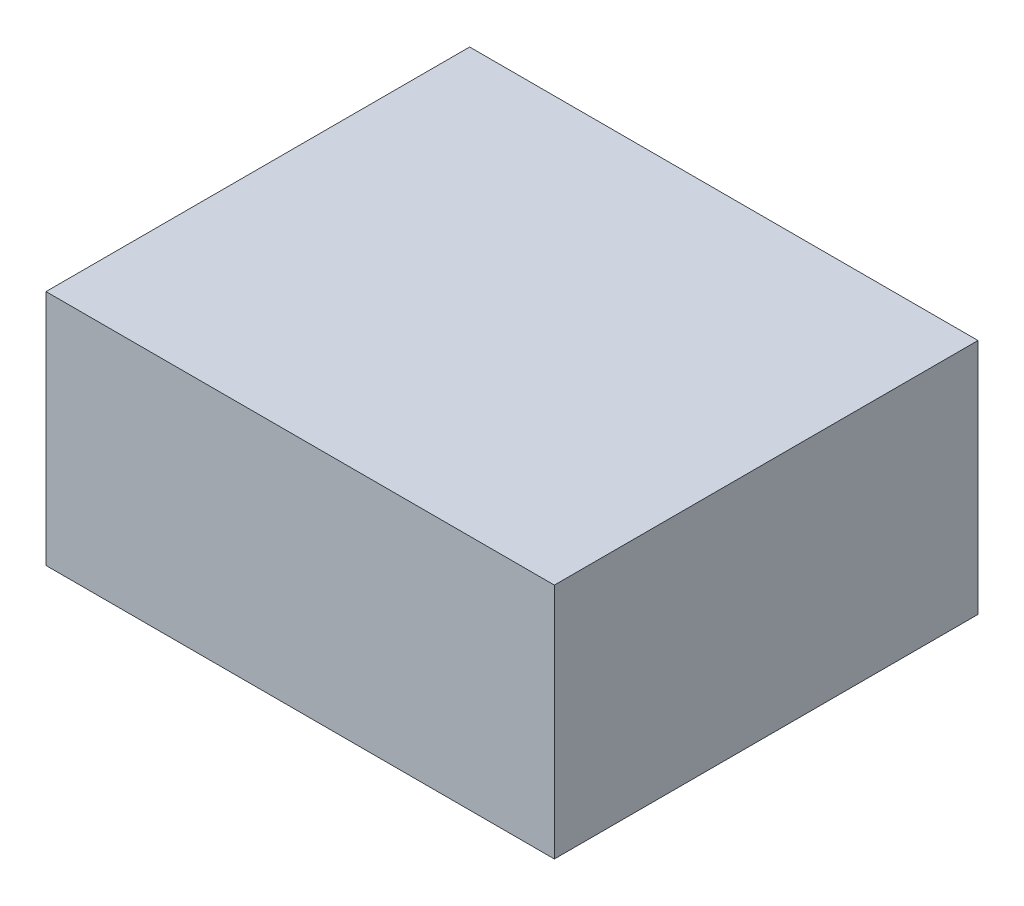
SolidWorks part; units mm, degrees
ref_plane "Front Plane" through (0, 0, 0) normal (0, 0, 1) x (1, 0, 0)
ref_plane "Top Plane" through (0, 0, 0) normal (0, 1, 0) x (1, 0, 0)
ref_plane "Right Plane" through (0, 0, 0) normal (1, 0, 0) x (0, 0, -1)
sketch "SK_Pack" plane through (0, 0, 0) normal (0, 0, 1) x (1, 0, 0)
  line L0 (-45, 0) -> (45, 0)
  line L1 (45, 0) -> (45, 42)
  line L2 (45, 42) -> (-45, 42)
  line L3 (-45, 42) -> (-45, 0)
extrude "Pack" add sketch "SK_Pack" along normal mid plane 75
